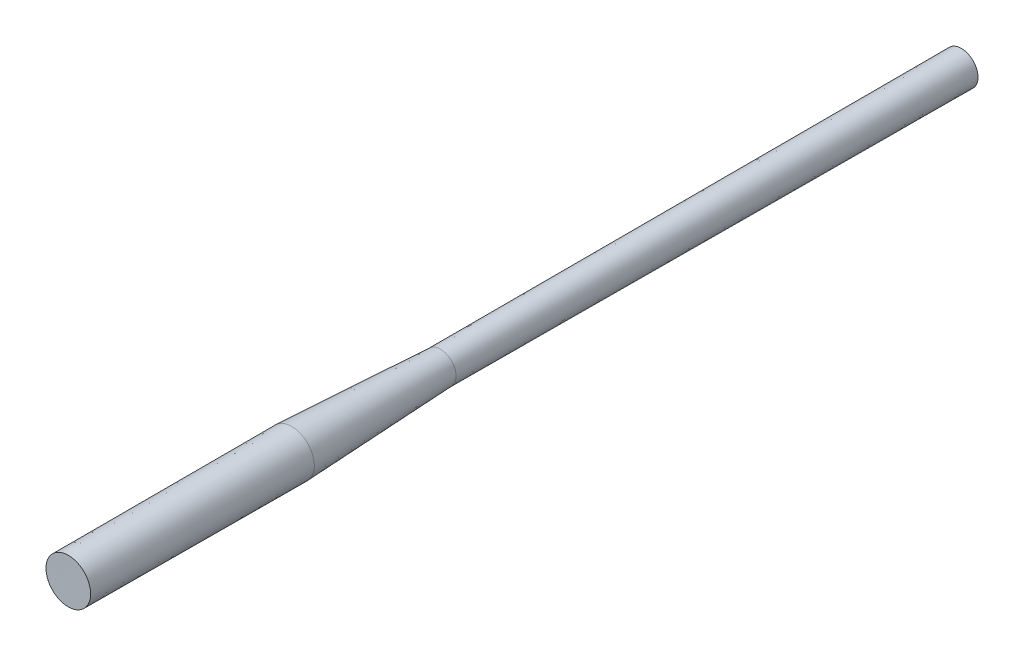
SolidWorks part; units mm, degrees
ref_plane "Front Plane" through (0, 0, 0) normal (0, 0, 1) x (1, 0, 0)
ref_plane "Top Plane" through (0, 0, 0) normal (0, 1, 0) x (1, 0, 0)
ref_plane "Right Plane" through (0, 0, 0) normal (1, 0, 0) x (0, 0, -1)
sketch "Sketch2" plane through (0, 0, 0) normal (1, 0, 0) x (0, 0, -1)
  line L0 (0, 76.2) -> (762, 76.2)
  line L1 (762, 76.2) -> (1270, 50.8)
  line L2 (1270, 50.8) -> (3048, 50.8)
  line L3 (0, 0) -> (1497.6952, 0) construction
  line L4 (0, 76.2) -> (0, 0)
  line L5 (0, 0) -> (3048, -6.2834)
  line L6 (3048, -6.2834) -> (3048, 50.8)
  dimension "D1" = 76.2
  dimension "D2" = 50.8
  dimension "D3" = 508
  dimension "D4" = 3048
  dimension "D5" = 762
  dimension "D6" = 3048
revolve "Revolve1" add sketch "Sketch2" angle 360 about L5
ref_plane "Plane1" through (76.1998, 0, 0.1571) normal (1, 0, 0.0021) x (0.0021, 0, -1)
